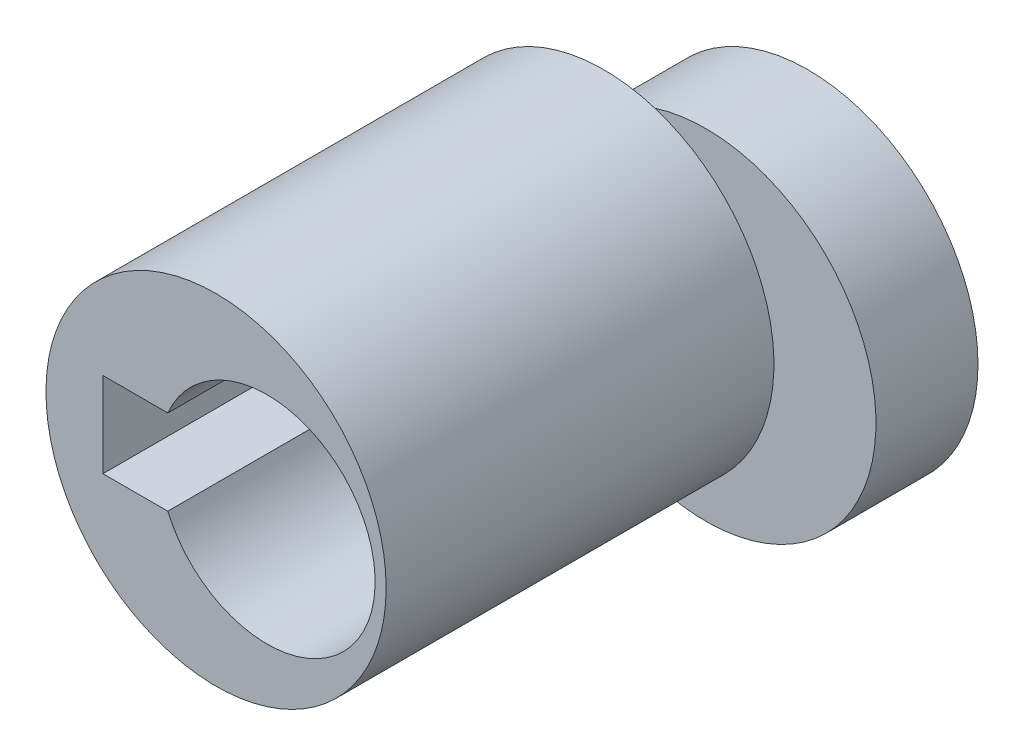
SolidWorks part; units mm, degrees
ref_plane "前视基准面" through (0, 0, 0) normal (0, 0, 1) x (1, 0, 0)
ref_plane "上视基准面" through (0, 0, 0) normal (0, 1, 0) x (1, 0, 0)
ref_plane "右视基准面" through (0, 0, 0) normal (1, 0, 0) x (0, 0, -1)
sketch "草图1" plane through (0, 0, 0) normal (0, 0, 1) x (1, 0, 0)
  circle A0 centre (0, 0) radius 10
  dimension "D1" = 20
extrude "凸台-拉伸1" add sketch "草图1" along normal blind 6
sketch "草图2" plane through (0, 0, 6) normal (0, 0, 1) x (1, 0, 0)
  circle A0 centre (-6, 0) radius 10
  dimension "D1" = 20
  dimension "D2" = 6
extrude "凸台-拉伸2" add sketch "草图2" along normal blind 22.8
sketch "草图3" plane through (0, 0, 28.8) normal (0, 0, 1) x (1, 0, 0)
  line L5 (-12.65, 2.5) -> (-8.8372, 2.5)
  line L6 (-12.65, 2.5) -> (-12.65, -2.5)
  line L7 (-12.65, -2.5) -> (-8.8372, -2.5)
  line L9 (-12.65, 2.5) -> (-10.373, 0) construction
  line L10 (-12.65, -2.5) -> (-9.0127, 1.4934) construction
  arc A2 (-8.8372, -2.5) -> (-8.8372, 2.5) centre (-3, 0) ccw
  point P3 (-10.373, 0)
  point P8 (0, 0)
  dimension "D1" = 12.7
  dimension "D2" = 3
  dimension "D3" = 5
  dimension "D4" = 2.5
  dimension "D5" = 9.65
extrude "切除-拉伸1" cut sketch "草图3" against normal blind 13
